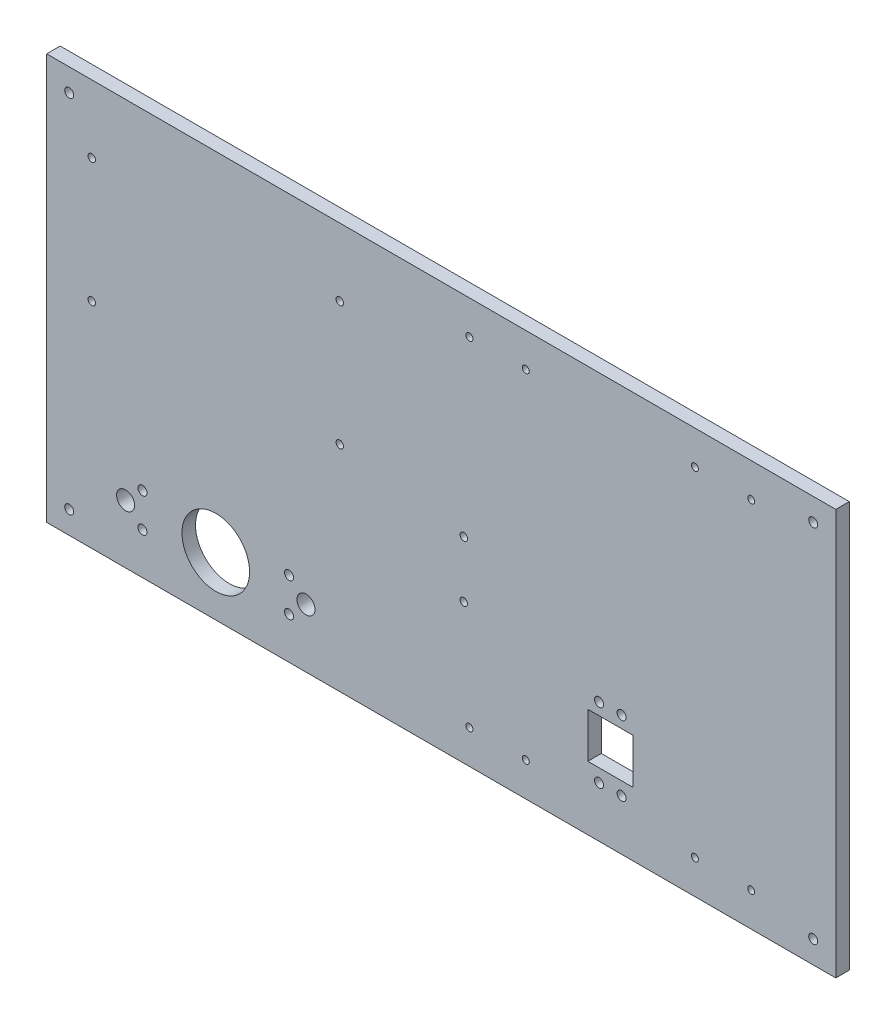
SolidWorks part; units mm, degrees
material "Faia"
ref_plane "Plano frontal" through (0, 0, 0) normal (0, 0, 1) x (1, 0, 0)
ref_plane "Plano superior" through (0, 0, 0) normal (0, 1, 0) x (1, 0, 0)
ref_plane "Plano direito" through (0, 0, 0) normal (1, 0, 0) x (0, 0, -1)
sketch "Esboço1" plane through (0, 0, 0) normal (0, 0, 1) x (1, 0, 0)
  line L0 (175, 0) -> (-175, 0) construction
  line L1 (-175, 90) -> (175, 90)
  line L2 (-175, 90) -> (-175, -90)
  line L3 (-175, -90) -> (175, -90)
  line L4 (175, 90) -> (175, -90)
  line L5 (-175, 90) -> (175, -90) construction
  line L6 (-175, -90) -> (175, 90) construction
  line L7 (95, 0) -> (-255, 0) construction
  line L8 (-108.2276, -64) -> (-89.3617, -64) construction
  line L9 (35, 5) -> (35, -80) construction
  line L10 (115, 5) -> (35, 5) construction
  line L11 (35, -80) -> (115, -80) construction
  line L12 (-100, -58.1086) -> (-100, -85.356) construction
  line L13 (65, -41.75) -> (85, -41.75)
  line L14 (65, -41.75) -> (65, -61.75)
  line L15 (65, -61.75) -> (85, -61.75)
  line L16 (85, -41.75) -> (85, -61.75)
  line L17 (65, -41.75) -> (85, -61.75) construction
  line L18 (65, -61.75) -> (85, -41.75) construction
  line L20 (-45, 5) -> (-155, 5) construction
  line L21 (-45, 5) -> (-45, 60) construction
  line L22 (-45, 60) -> (-155, 60) construction
  line L23 (-155, 5) -> (-155, 60) construction
  line L24 (-45, 5) -> (-155, 60) construction
  line L25 (-45, 60) -> (-155, 5) construction
  circle A0 centre (115, 5) radius 1.5 construction
  circle A1 centre (115, -80) radius 1.5 construction
  circle A2 centre (35, -80) radius 1.5 construction
  circle A3 centre (35, 5) radius 1.5 construction
  circle A4 centre (-132.5, -56.5) radius 2
  circle A5 centre (-67.5, -56.5) radius 2
  circle A6 centre (-100, -64) radius 15
  circle A7 centre (-60, -64) radius 4
  circle A8 centre (-140, -64) radius 4
  circle A9 centre (-67.5, -71.5) radius 2
  circle A10 centre (-132.5, -71.5) radius 2
  circle A11 centre (10, -3) radius 1.65
  circle A12 centre (10, -28) radius 1.65
  circle A13 centre (-155, 60) radius 1.65
  circle A14 centre (-45, 60) radius 1.65
  circle A15 centre (-45, 5) radius 1.65
  circle A16 centre (-155, 5) radius 1.65
  point P0 (0, 0)
  point P21 (5, 0)
  point P23 (75, -51.75)
  point P28 (75, -80)
  point P48 (-100, 32.5)
  point P56 (0, 0)
  point P57 (0, 0)
  dimension "D5" = 3
  dimension "D8" = 32.5
  dimension "D16" = 30
  dimension "D19" = 8
  dimension "D20" = 80
  dimension "D10" = 4
  dimension "D21" = 3.3
  dimension "D26" = 3.3
  dimension "D1" = 350
  dimension "D2" = 180
  dimension "D3" = 60
  dimension "D4" = 85
  dimension "D7" = 80
  dimension "D9" = 15
  dimension "D11" = 25
  dimension "D12" = 10
  dimension "D13" = 20
  dimension "D14" = 20
  dimension "D15" = 28.25
  dimension "D17" = 75
  dimension "D18" = 26
  dimension "D22" = 25
  dimension "D23" = 8
  dimension "D24" = 55
  dimension "D25" = 110
  dimension "D27" = 30
  dimension "D28" = 20
  dimension "D6" = 2
extrude "Ressalto-extrusão1" add sketch "Esboço1" along normal blind 6 contours L4 L1 L2 L3 A3 A1 A0 A2
sketch "Esboço2" plane through (0, 0, 6) normal (0, 0, 1) x (1, 0, 0)
  line L0 (175, 0) -> (-175, 0) construction
  line L1 (-175, 90) -> (175, 90)
  line L2 (-175, 90) -> (-175, -90)
  line L3 (-175, -90) -> (175, -90)
  line L4 (175, 90) -> (175, -90)
  line L5 (-175, 90) -> (175, -90) construction
  line L6 (-175, -90) -> (175, 90) construction
  line L7 (165, 80) -> (165, 90) construction
  line L8 (165, -80) -> (165, -90) construction
  line L9 (-175, 90) -> (175, 90) construction
  circle A0 centre (165, -80) radius 2
  circle A1 centre (165, 80) radius 2
  circle A2 centre (-165, 80) radius 2
  circle A3 centre (-165, -80) radius 2
  point P0 (0, 0)
  point P16 (0.5357, 0)
  dimension "D3" = 4
  dimension "D2" = 180
  dimension "D4" = 10
  dimension "D5" = 10
  dimension "D6" = 10
  dimension "D7" = 10
extrude "Corte-extrusão1" cut sketch "Esboço2" against normal blind 10 contours A2 | A1 | A0 | A3
sketch "Esboço3" plane through (0, 0, 6) normal (0, 0, 1) x (1, 0, 0)
  line L1 (-175, -90) -> (175, -90) construction
  line L2 (70, -67.5) -> (80, -67.5) construction
  line L3 (65, -61.75) -> (85, -61.75) construction
  circle A0 centre (80, -67.5) radius 2
  circle A1 centre (80, -36.5) radius 2
  circle A2 centre (70, -36.5) radius 2
  circle A3 centre (70, -67.5) radius 2
  point P2 (75, -67.5)
  point P13 (75, -61.75)
  dimension "D2" = 4
  dimension "D3" = 22.5
  dimension "D4" = 31
  dimension "D5" = 10
extrude "Corte-extrusão2" cut sketch "Esboço3" against normal blind 10
sketch "Esboço4" plane through (0, 0, 6) normal (0, 0, 1) x (1, 0, 0)
  line L0 (112.5, 75) -> (137.5, 75) construction
  line L1 (12.5, 75) -> (37.5, 75) construction
  line L2 (75, -41.75) -> (75, 53.8452) construction
  line L3 (65, -41.75) -> (85, -41.75) construction
  line L4 (137.5, -75) -> (112.5, -75) construction
  line L5 (12.5, -75) -> (37.5, -75) construction
  line L6 (175, 0) -> (131.6351, 0) construction
  line L7 (175, 90) -> (175, -90) construction
  circle A0 centre (112.5, 75) radius 1.55
  circle A1 centre (137.5, 75) radius 1.55
  circle A2 centre (12.5, 75) radius 1.55
  circle A3 centre (37.5, 75) radius 1.55
  circle A4 centre (137.5, -75) radius 1.55
  circle A5 centre (112.5, -75) radius 1.55
  circle A6 centre (12.5, -75) radius 1.55
  circle A7 centre (37.5, -75) radius 1.55
  point P8 (25, 75)
  point P9 (125, 75)
  point P22 (25, -75)
  point P23 (125, -75)
  point P24 (137.5, -75)
  point P30 (0, 0)
  point P31 (0, 0)
  dimension "D2" = 3.1
  dimension "D4" = 3.1
  dimension "D1" = 25
  dimension "D3" = 150
  dimension "D5" = 100
extrude "Corte-extrusão3" cut sketch "Esboço4" against normal blind 10
